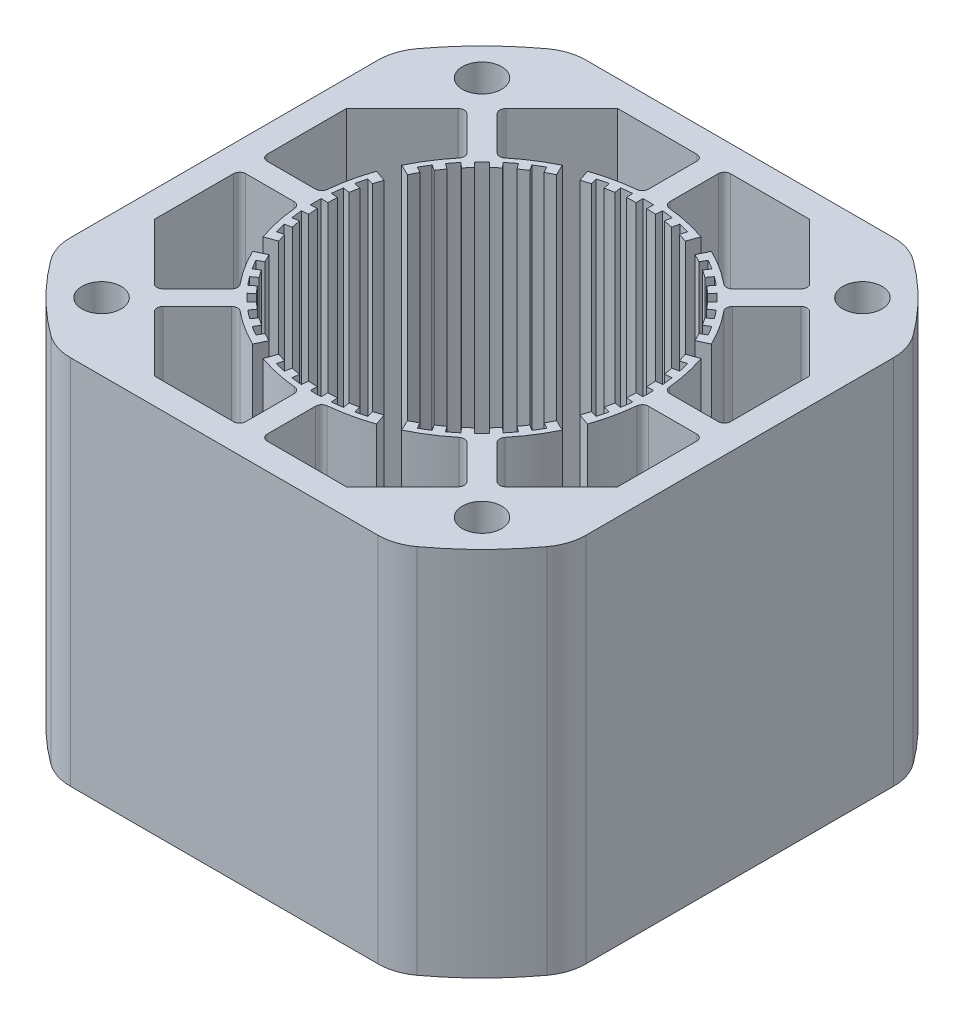
SolidWorks part; units mm, degrees
ref_plane "Front" through (0, 0, 0) normal (0, 0, 1) x (1, 0, 0)
ref_plane "Top" through (0, 0, 0) normal (0, 1, 0) x (1, 0, 0)
ref_plane "Right" through (0, 0, 0) normal (1, 0, 0) x (0, 0, -1)
ref_plane "Plane1" through (0, 10.95, 0) normal (0, 1, 0) x (1, 0, 0)
sketch "Sketch1" plane through (0, 10.95, 0) normal (0, 1, 0) x (1, 0, 0)
  line L0 (-0.875, -14.4347) -> (-0.875, -18.375)
  line L1 (-1.375, -18.875) -> (-7.8183, -18.875)
  line L2 (-7.8183, -18.875) -> (-12.3744, -14.3189)
  line L3 (-12.3744, -13.6118) -> (-9.5881, -10.8256)
  line L4 (-6.0745, -12.6135) -> (-5.6406, -11.7126)
  line L5 (-6.3066, -11.3678) -> (-6.5735, -11.8487)
  line L6 (-7.3337, -11.3938) -> (-7.036, -10.9313)
  line L7 (-7.6547, -10.5074) -> (-7.9786, -10.9519)
  line L8 (-8.6772, -10.4071) -> (-8.325, -9.9847)
  line L9 (-8.887, -9.488) -> (-9.2629, -9.8894)
  line L10 (-9.8894, -9.2629) -> (-9.488, -8.887)
  line L11 (-9.9847, -8.325) -> (-10.4071, -8.6772)
  line L12 (-10.9519, -7.9786) -> (-10.5074, -7.6547)
  line L13 (-10.9313, -7.036) -> (-11.3938, -7.3337)
  line L14 (-11.8487, -6.5735) -> (-11.3678, -6.3066)
  line L15 (-11.7126, -5.6406) -> (-12.6135, -6.0745)
  line L16 (-10.8256, -9.5881) -> (-13.6118, -12.3744)
  line L17 (-14.3189, -12.3744) -> (-18.875, -7.8183)
  line L18 (-18.875, -7.8183) -> (-18.875, -1.375)
  line L19 (-18.375, -0.875) -> (-14.4347, -0.875)
  line L20 (-13.2144, -4.6238) -> (-12.2705, -4.2935)
  line L21 (-12.4977, -3.5788) -> (-13.0264, -3.7302)
  line L22 (-13.2424, -2.8709) -> (-12.7049, -2.7544)
  line L23 (-12.8426, -2.0171) -> (-13.3859, -2.1025)
  line L24 (-13.4947, -1.2232) -> (-12.9469, -1.1736)
  line L25 (-12.9931, -0.425) -> (-13.5428, -0.443)
  line L26 (-13.5428, 0.443) -> (-12.9931, 0.425)
  line L27 (-12.9469, 1.1736) -> (-13.4947, 1.2232)
  line L28 (-13.3859, 2.1025) -> (-12.8426, 2.0171)
  line L29 (-12.7049, 2.7544) -> (-13.2424, 2.8709)
  line L30 (-13.0264, 3.7302) -> (-12.4977, 3.5788)
  line L31 (-12.2705, 4.2935) -> (-13.2144, 4.6238)
  line L32 (-14.4347, 0.875) -> (-18.375, 0.875)
  line L33 (-18.875, 1.375) -> (-18.875, 7.8183)
  line L34 (-18.875, 7.8183) -> (-14.3189, 12.3744)
  line L35 (-13.6118, 12.3744) -> (-10.8256, 9.5881)
  line L36 (-12.6135, 6.0745) -> (-11.7126, 5.6406)
  line L37 (-11.3678, 6.3066) -> (-11.8487, 6.5735)
  line L38 (-11.3938, 7.3337) -> (-10.9313, 7.036)
  line L39 (-10.5074, 7.6547) -> (-10.9519, 7.9786)
  line L40 (-10.4071, 8.6772) -> (-9.9847, 8.325)
  line L41 (-9.488, 8.887) -> (-9.8894, 9.2629)
  line L42 (-9.2629, 9.8894) -> (-8.887, 9.488)
  line L43 (-8.325, 9.9847) -> (-8.6772, 10.4071)
  line L44 (-7.9786, 10.9519) -> (-7.6547, 10.5074)
  line L45 (-7.036, 10.9313) -> (-7.3337, 11.3938)
  line L46 (-6.5735, 11.8487) -> (-6.3066, 11.3678)
  line L47 (-5.6406, 11.7126) -> (-6.0745, 12.6135)
  line L48 (-9.5881, 10.8256) -> (-12.3744, 13.6118)
  line L49 (-12.3744, 14.3189) -> (-7.8183, 18.875)
  line L50 (-7.8183, 18.875) -> (-1.375, 18.875)
  line L51 (-0.875, 18.375) -> (-0.875, 14.4347)
  line L52 (-4.6238, 13.2144) -> (-4.2935, 12.2705)
  line L53 (-3.5788, 12.4977) -> (-3.7302, 13.0264)
  line L54 (-2.8709, 13.2424) -> (-2.7544, 12.7049)
  line L55 (-2.0171, 12.8426) -> (-2.1025, 13.3859)
  line L56 (-1.2232, 13.4947) -> (-1.1736, 12.9469)
  line L57 (-0.425, 12.9931) -> (-0.443, 13.5428)
  line L58 (0.443, 13.5428) -> (0.425, 12.9931)
  line L59 (1.1736, 12.9469) -> (1.2232, 13.4947)
  line L60 (2.1025, 13.3859) -> (2.0171, 12.8426)
  line L61 (2.7544, 12.7049) -> (2.8709, 13.2424)
  line L62 (3.7302, 13.0264) -> (3.5788, 12.4977)
  line L63 (4.2935, 12.2705) -> (4.6238, 13.2144)
  line L64 (0.875, 14.4347) -> (0.875, 18.375)
  line L65 (1.375, 18.875) -> (7.8183, 18.875)
  line L66 (7.8183, 18.875) -> (12.3744, 14.3189)
  line L67 (12.3744, 13.6118) -> (9.5881, 10.8256)
  line L68 (6.0745, 12.6135) -> (5.6406, 11.7126)
  line L69 (6.3066, 11.3678) -> (6.5735, 11.8487)
  line L70 (7.3337, 11.3938) -> (7.036, 10.9313)
  line L71 (7.6547, 10.5074) -> (7.9786, 10.9519)
  line L72 (8.6772, 10.4071) -> (8.325, 9.9847)
  line L73 (8.887, 9.488) -> (9.2629, 9.8894)
  line L74 (9.8894, 9.2629) -> (9.488, 8.887)
  line L75 (9.9847, 8.325) -> (10.4071, 8.6772)
  line L76 (10.9519, 7.9786) -> (10.5074, 7.6547)
  line L77 (10.9313, 7.036) -> (11.3938, 7.3337)
  line L78 (11.8487, 6.5735) -> (11.3678, 6.3066)
  line L79 (11.7126, 5.6406) -> (12.6135, 6.0745)
  line L80 (10.8256, 9.5881) -> (13.6118, 12.3744)
  line L81 (14.3189, 12.3744) -> (18.875, 7.8183)
  line L82 (18.875, 7.8183) -> (18.875, 1.375)
  line L83 (18.375, 0.875) -> (14.4347, 0.875)
  line L84 (13.2144, 4.6238) -> (12.2705, 4.2935)
  line L85 (12.4977, 3.5788) -> (13.0264, 3.7302)
  line L86 (13.2424, 2.8709) -> (12.7049, 2.7544)
  line L87 (12.8426, 2.0171) -> (13.3859, 2.1025)
  line L88 (13.4947, 1.2232) -> (12.9469, 1.1736)
  line L89 (12.9931, 0.425) -> (13.5428, 0.443)
  line L90 (13.5428, -0.443) -> (12.9931, -0.425)
  line L91 (12.9469, -1.1736) -> (13.4947, -1.2232)
  line L92 (13.3859, -2.1025) -> (12.8426, -2.0171)
  line L93 (12.7049, -2.7544) -> (13.2424, -2.8709)
  line L94 (13.0264, -3.7302) -> (12.4977, -3.5788)
  line L95 (12.2705, -4.2935) -> (13.2144, -4.6238)
  line L96 (14.4347, -0.875) -> (18.375, -0.875)
  line L97 (18.875, -1.375) -> (18.875, -7.8183)
  line L98 (18.875, -7.8183) -> (14.3189, -12.3744)
  line L99 (13.6118, -12.3744) -> (10.8256, -9.5881)
  line L100 (12.6135, -6.0745) -> (11.7126, -5.6406)
  line L101 (11.3678, -6.3066) -> (11.8487, -6.5735)
  line L102 (11.3938, -7.3337) -> (10.9313, -7.036)
  line L103 (10.5074, -7.6547) -> (10.9519, -7.9786)
  line L104 (10.4071, -8.6772) -> (9.9847, -8.325)
  line L105 (9.488, -8.887) -> (9.8894, -9.2629)
  line L106 (9.2629, -9.8894) -> (8.887, -9.488)
  line L107 (8.325, -9.9847) -> (8.6772, -10.4071)
  line L108 (7.9786, -10.9519) -> (7.6547, -10.5074)
  line L109 (7.036, -10.9313) -> (7.3337, -11.3938)
  line L110 (6.5735, -11.8487) -> (6.3066, -11.3678)
  line L111 (5.6406, -11.7126) -> (6.0745, -12.6135)
  line L112 (9.5881, -10.8256) -> (12.3744, -13.6118)
  line L113 (12.3744, -14.3189) -> (7.8183, -18.875)
  line L114 (7.8183, -18.875) -> (1.375, -18.875)
  line L115 (0.875, -18.375) -> (0.875, -14.4347)
  line L116 (4.6238, -13.2144) -> (4.2935, -12.2705)
  line L117 (3.5788, -12.4977) -> (3.7302, -13.0264)
  line L118 (2.8709, -13.2424) -> (2.7544, -12.7049)
  line L119 (2.0171, -12.8426) -> (2.1025, -13.3859)
  line L120 (1.2232, -13.4947) -> (1.1736, -12.9469)
  line L121 (0.425, -12.9931) -> (0.443, -13.5428)
  line L122 (-0.443, -13.5428) -> (-0.425, -12.9931)
  line L123 (-1.1736, -12.9469) -> (-1.2232, -13.4947)
  line L124 (-2.1025, -13.3859) -> (-2.0171, -12.8426)
  line L125 (-2.7544, -12.7049) -> (-2.8709, -13.2424)
  line L126 (-3.7302, -13.0264) -> (-3.5788, -12.4977)
  line L127 (-4.2935, -12.2705) -> (-4.6238, -13.2144)
  line L128 (21, -12.5406) -> (21, 12.5406)
  line L129 (12.5406, 21) -> (-12.5406, 21)
  line L130 (-21, 12.5406) -> (-21, -12.5406)
  line L131 (-12.5406, -21) -> (12.5406, -21)
  arc A0 (-0.875, -18.375) -> (-1.375, -18.875) centre (-1.375, -18.375) cw
  arc A1 (-12.3744, -14.3189) -> (-12.3744, -13.6118) centre (-12.0208, -13.9654) cw
  arc A2 (-9.5881, -10.8256) -> (-8.9161, -10.7936) centre (-9.2346, -11.1791) cw
  arc A3 (-8.9161, -10.7936) -> (-6.0745, -12.6135) centre (0, 0) ccw
  arc A4 (-5.6406, -11.7126) -> (-6.3066, -11.3678) centre (0, 0) cw
  arc A5 (-6.5735, -11.8487) -> (-7.3337, -11.3938) centre (0, 0) cw
  arc A6 (-7.036, -10.9313) -> (-7.6547, -10.5074) centre (0, 0) cw
  arc A7 (-7.9786, -10.9519) -> (-8.6772, -10.4071) centre (0, 0) cw
  arc A8 (-8.325, -9.9847) -> (-8.887, -9.488) centre (0, 0) cw
  arc A9 (-9.2629, -9.8894) -> (-9.8894, -9.2629) centre (0, 0) cw
  arc A10 (-9.488, -8.887) -> (-9.9847, -8.325) centre (0, 0) cw
  arc A11 (-10.4071, -8.6772) -> (-10.9519, -7.9786) centre (0, 0) cw
  arc A12 (-10.5074, -7.6547) -> (-10.9313, -7.036) centre (0, 0) cw
  arc A13 (-11.3938, -7.3337) -> (-11.8487, -6.5735) centre (0, 0) cw
  arc A14 (-11.3678, -6.3066) -> (-11.7126, -5.6406) centre (0, 0) cw
  arc A15 (-12.6135, -6.0745) -> (-10.7936, -8.9161) centre (0, 0) ccw
  arc A16 (-10.7936, -8.9161) -> (-10.8256, -9.5881) centre (-11.1791, -9.2346) cw
  arc A17 (-13.6118, -12.3744) -> (-14.3189, -12.3744) centre (-13.9654, -12.0208) cw
  arc A18 (-18.875, -1.375) -> (-18.375, -0.875) centre (-18.375, -1.375) cw
  arc A19 (-14.4347, -0.875) -> (-13.9369, -1.3276) centre (-14.4347, -1.375) cw
  arc A20 (-13.9369, -1.3276) -> (-13.2144, -4.6238) centre (0, 0) ccw
  arc A21 (-12.2705, -4.2935) -> (-12.4977, -3.5788) centre (0, 0) cw
  arc A22 (-13.0264, -3.7302) -> (-13.2424, -2.8709) centre (0, 0) cw
  arc A23 (-12.7049, -2.7544) -> (-12.8426, -2.0171) centre (0, 0) cw
  arc A24 (-13.3859, -2.1025) -> (-13.4947, -1.2232) centre (0, 0) cw
  arc A25 (-12.9469, -1.1736) -> (-12.9931, -0.425) centre (0, 0) cw
  arc A26 (-13.5428, -0.443) -> (-13.5428, 0.443) centre (0, 0) cw
  arc A27 (-12.9931, 0.425) -> (-12.9469, 1.1736) centre (0, 0) cw
  arc A28 (-13.4947, 1.2232) -> (-13.3859, 2.1025) centre (0, 0) cw
  arc A29 (-12.8426, 2.0171) -> (-12.7049, 2.7544) centre (0, 0) cw
  arc A30 (-13.2424, 2.8709) -> (-13.0264, 3.7302) centre (0, 0) cw
  arc A31 (-12.4977, 3.5788) -> (-12.2705, 4.2935) centre (0, 0) cw
  arc A32 (-13.2144, 4.6238) -> (-13.9369, 1.3276) centre (0, 0) ccw
  arc A33 (-13.9369, 1.3276) -> (-14.4347, 0.875) centre (-14.4347, 1.375) cw
  arc A34 (-18.375, 0.875) -> (-18.875, 1.375) centre (-18.375, 1.375) cw
  arc A35 (-14.3189, 12.3744) -> (-13.6118, 12.3744) centre (-13.9654, 12.0208) cw
  arc A36 (-10.8256, 9.5881) -> (-10.7936, 8.9161) centre (-11.1791, 9.2346) cw
  arc A37 (-10.7936, 8.9161) -> (-12.6135, 6.0745) centre (0, 0) ccw
  arc A38 (-11.7126, 5.6406) -> (-11.3678, 6.3066) centre (0, 0) cw
  arc A39 (-11.8487, 6.5735) -> (-11.3938, 7.3337) centre (0, 0) cw
  arc A40 (-10.9313, 7.036) -> (-10.5074, 7.6547) centre (0, 0) cw
  arc A41 (-10.9519, 7.9786) -> (-10.4071, 8.6772) centre (0, 0) cw
  arc A42 (-9.9847, 8.325) -> (-9.488, 8.887) centre (0, 0) cw
  arc A43 (-9.8894, 9.2629) -> (-9.2629, 9.8894) centre (0, 0) cw
  arc A44 (-8.887, 9.488) -> (-8.325, 9.9847) centre (0, 0) cw
  arc A45 (-8.6772, 10.4071) -> (-7.9786, 10.9519) centre (0, 0) cw
  arc A46 (-7.6547, 10.5074) -> (-7.036, 10.9313) centre (0, 0) cw
  arc A47 (-7.3337, 11.3938) -> (-6.5735, 11.8487) centre (0, 0) cw
  arc A48 (-6.3066, 11.3678) -> (-5.6406, 11.7126) centre (0, 0) cw
  arc A49 (-6.0745, 12.6135) -> (-8.9161, 10.7936) centre (0, 0) ccw
  arc A50 (-8.9161, 10.7936) -> (-9.5881, 10.8256) centre (-9.2346, 11.1791) cw
  arc A51 (-12.3744, 13.6118) -> (-12.3744, 14.3189) centre (-12.0208, 13.9654) cw
  arc A52 (-1.375, 18.875) -> (-0.875, 18.375) centre (-1.375, 18.375) cw
  arc A53 (-0.875, 14.4347) -> (-1.3276, 13.9369) centre (-1.375, 14.4347) cw
  arc A54 (-1.3276, 13.9369) -> (-4.6238, 13.2144) centre (0, 0) ccw
  arc A55 (-4.2935, 12.2705) -> (-3.5788, 12.4977) centre (0, 0) cw
  arc A56 (-3.7302, 13.0264) -> (-2.8709, 13.2424) centre (0, 0) cw
  arc A57 (-2.7544, 12.7049) -> (-2.0171, 12.8426) centre (0, 0) cw
  arc A58 (-2.1025, 13.3859) -> (-1.2232, 13.4947) centre (0, 0) cw
  arc A59 (-1.1736, 12.9469) -> (-0.425, 12.9931) centre (0, 0) cw
  arc A60 (-0.443, 13.5428) -> (0.443, 13.5428) centre (0, 0) cw
  arc A61 (0.425, 12.9931) -> (1.1736, 12.9469) centre (0, 0) cw
  arc A62 (1.2232, 13.4947) -> (2.1025, 13.3859) centre (0, 0) cw
  arc A63 (2.0171, 12.8426) -> (2.7544, 12.7049) centre (0, 0) cw
  arc A64 (2.8709, 13.2424) -> (3.7302, 13.0264) centre (0, 0) cw
  arc A65 (3.5788, 12.4977) -> (4.2935, 12.2705) centre (0, 0) cw
  arc A66 (4.6238, 13.2144) -> (1.3276, 13.9369) centre (0, 0) ccw
  arc A67 (1.3276, 13.9369) -> (0.875, 14.4347) centre (1.375, 14.4347) cw
  arc A68 (0.875, 18.375) -> (1.375, 18.875) centre (1.375, 18.375) cw
  arc A69 (12.3744, 14.3189) -> (12.3744, 13.6118) centre (12.0208, 13.9654) cw
  arc A70 (9.5881, 10.8256) -> (8.9161, 10.7936) centre (9.2346, 11.1791) cw
  arc A71 (8.9161, 10.7936) -> (6.0745, 12.6135) centre (0, 0) ccw
  arc A72 (5.6406, 11.7126) -> (6.3066, 11.3678) centre (0, 0) cw
  arc A73 (6.5735, 11.8487) -> (7.3337, 11.3938) centre (0, 0) cw
  arc A74 (7.036, 10.9313) -> (7.6547, 10.5074) centre (0, 0) cw
  arc A75 (7.9786, 10.9519) -> (8.6772, 10.4071) centre (0, 0) cw
  arc A76 (8.325, 9.9847) -> (8.887, 9.488) centre (0, 0) cw
  arc A77 (9.2629, 9.8894) -> (9.8894, 9.2629) centre (0, 0) cw
  arc A78 (9.488, 8.887) -> (9.9847, 8.325) centre (0, 0) cw
  arc A79 (10.4071, 8.6772) -> (10.9519, 7.9786) centre (0, 0) cw
  arc A80 (10.5074, 7.6547) -> (10.9313, 7.036) centre (0, 0) cw
  arc A81 (11.3938, 7.3337) -> (11.8487, 6.5735) centre (0, 0) cw
  arc A82 (11.3678, 6.3066) -> (11.7126, 5.6406) centre (0, 0) cw
  arc A83 (12.6135, 6.0745) -> (10.7936, 8.9161) centre (0, 0) ccw
  arc A84 (10.7936, 8.9161) -> (10.8256, 9.5881) centre (11.1791, 9.2346) cw
  arc A85 (13.6118, 12.3744) -> (14.3189, 12.3744) centre (13.9654, 12.0208) cw
  arc A86 (18.875, 1.375) -> (18.375, 0.875) centre (18.375, 1.375) cw
  arc A87 (14.4347, 0.875) -> (13.9369, 1.3276) centre (14.4347, 1.375) cw
  arc A88 (13.9369, 1.3276) -> (13.2144, 4.6238) centre (0, 0) ccw
  arc A89 (12.2705, 4.2935) -> (12.4977, 3.5788) centre (0, 0) cw
  arc A90 (13.0264, 3.7302) -> (13.2424, 2.8709) centre (0, 0) cw
  arc A91 (12.7049, 2.7544) -> (12.8426, 2.0171) centre (0, 0) cw
  arc A92 (13.3859, 2.1025) -> (13.4947, 1.2232) centre (0, 0) cw
  arc A93 (12.9469, 1.1736) -> (12.9931, 0.425) centre (0, 0) cw
  arc A94 (13.5428, 0.443) -> (13.5428, -0.443) centre (0, 0) cw
  arc A95 (12.9931, -0.425) -> (12.9469, -1.1736) centre (0, 0) cw
  arc A96 (13.4947, -1.2232) -> (13.3859, -2.1025) centre (0, 0) cw
  arc A97 (12.8426, -2.0171) -> (12.7049, -2.7544) centre (0, 0) cw
  arc A98 (13.2424, -2.8709) -> (13.0264, -3.7302) centre (0, 0) cw
  arc A99 (12.4977, -3.5788) -> (12.2705, -4.2935) centre (0, 0) cw
  arc A100 (13.2144, -4.6238) -> (13.9369, -1.3276) centre (0, 0) ccw
  arc A101 (13.9369, -1.3276) -> (14.4347, -0.875) centre (14.4347, -1.375) cw
  arc A102 (18.375, -0.875) -> (18.875, -1.375) centre (18.375, -1.375) cw
  arc A103 (14.3189, -12.3744) -> (13.6118, -12.3744) centre (13.9654, -12.0208) cw
  arc A104 (10.8256, -9.5881) -> (10.7936, -8.9161) centre (11.1791, -9.2346) cw
  arc A105 (10.7936, -8.9161) -> (12.6135, -6.0745) centre (0, 0) ccw
  arc A106 (11.7126, -5.6406) -> (11.3678, -6.3066) centre (0, 0) cw
  arc A107 (11.8487, -6.5735) -> (11.3938, -7.3337) centre (0, 0) cw
  arc A108 (10.9313, -7.036) -> (10.5074, -7.6547) centre (0, 0) cw
  arc A109 (10.9519, -7.9786) -> (10.4071, -8.6772) centre (0, 0) cw
  arc A110 (9.9847, -8.325) -> (9.488, -8.887) centre (0, 0) cw
  arc A111 (9.8894, -9.2629) -> (9.2629, -9.8894) centre (0, 0) cw
  arc A112 (8.887, -9.488) -> (8.325, -9.9847) centre (0, 0) cw
  arc A113 (8.6772, -10.4071) -> (7.9786, -10.9519) centre (0, 0) cw
  arc A114 (7.6547, -10.5074) -> (7.036, -10.9313) centre (0, 0) cw
  arc A115 (7.3337, -11.3938) -> (6.5735, -11.8487) centre (0, 0) cw
  arc A116 (6.3066, -11.3678) -> (5.6406, -11.7126) centre (0, 0) cw
  arc A117 (6.0745, -12.6135) -> (8.9161, -10.7936) centre (0, 0) ccw
  arc A118 (8.9161, -10.7936) -> (9.5881, -10.8256) centre (9.2346, -11.1791) cw
  arc A119 (12.3744, -13.6118) -> (12.3744, -14.3189) centre (12.0208, -13.9654) cw
  arc A120 (1.375, -18.875) -> (0.875, -18.375) centre (1.375, -18.375) cw
  arc A121 (0.875, -14.4347) -> (1.3276, -13.9369) centre (1.375, -14.4347) cw
  arc A122 (1.3276, -13.9369) -> (4.6238, -13.2144) centre (0, 0) ccw
  arc A123 (4.2935, -12.2705) -> (3.5788, -12.4977) centre (0, 0) cw
  arc A124 (3.7302, -13.0264) -> (2.8709, -13.2424) centre (0, 0) cw
  arc A125 (2.7544, -12.7049) -> (2.0171, -12.8426) centre (0, 0) cw
  arc A126 (2.1025, -13.3859) -> (1.2232, -13.4947) centre (0, 0) cw
  arc A127 (1.1736, -12.9469) -> (0.425, -12.9931) centre (0, 0) cw
  arc A128 (0.443, -13.5428) -> (-0.443, -13.5428) centre (0, 0) cw
  arc A129 (-0.425, -12.9931) -> (-1.1736, -12.9469) centre (0, 0) cw
  arc A130 (-1.2232, -13.4947) -> (-2.1025, -13.3859) centre (0, 0) cw
  arc A131 (-2.0171, -12.8426) -> (-2.7544, -12.7049) centre (0, 0) cw
  arc A132 (-2.8709, -13.2424) -> (-3.7302, -13.0264) centre (0, 0) cw
  arc A133 (-3.5788, -12.4977) -> (-4.2935, -12.2705) centre (0, 0) cw
  arc A134 (-4.6238, -13.2144) -> (-1.3276, -13.9369) centre (0, 0) ccw
  arc A135 (-1.3276, -13.9369) -> (-0.875, -14.4347) centre (-1.375, -14.4347) cw
  arc A136 (14.9151, -20.2189) -> (20.2189, -14.9151) centre (0, 0) ccw
  arc A137 (20.2189, -14.9151) -> (21, -12.5406) centre (17, -12.5406) ccw
  arc A138 (21, 12.5406) -> (20.2189, 14.9151) centre (17, 12.5406) ccw
  arc A139 (20.2189, 14.9151) -> (14.9151, 20.2189) centre (0, 0) ccw
  arc A140 (14.9151, 20.2189) -> (12.5406, 21) centre (12.5406, 17) ccw
  arc A141 (-12.5406, 21) -> (-14.9151, 20.2189) centre (-12.5406, 17) ccw
  arc A142 (-14.9151, 20.2189) -> (-20.2189, 14.9151) centre (0, 0) ccw
  arc A143 (-20.2189, 14.9151) -> (-21, 12.5406) centre (-17, 12.5406) ccw
  arc A144 (-21, -12.5406) -> (-20.2189, -14.9151) centre (-17, -12.5406) ccw
  arc A145 (-20.2189, -14.9151) -> (-14.9151, -20.2189) centre (0, 0) ccw
  arc A146 (-14.9151, -20.2189) -> (-12.5406, -21) centre (-12.5406, -17) ccw
  arc A147 (12.5406, -21) -> (14.9151, -20.2189) centre (12.5406, -17) ccw
sketch "Sketch10" plane through (0, 0, 0) normal (0, 1, 0) x (1, 0, 0)
  line L4 (12.5406, 21) -> (-12.5406, 21)
  line L5 (-21, 12.5406) -> (-21, -12.5406)
  line L6 (-12.5406, -21) -> (12.5406, -21)
  line L7 (21, -12.5406) -> (21, 12.5406)
  line L10 (7.8183, -18.875) -> (18.875, -7.8183)
  line L11 (18.875, -7.8183) -> (18.875, 7.8183)
  line L12 (18.875, 7.8183) -> (7.8183, 18.875)
  line L13 (7.8183, 18.875) -> (-7.8183, 18.875)
  line L14 (-7.8183, 18.875) -> (-18.875, 7.8183)
  line L15 (-18.875, 7.8183) -> (-18.875, -7.8183)
  line L16 (-18.875, -7.8183) -> (-7.8183, -18.875)
  line L17 (0, 21) -> (0, 0) construction
  line L18 (0, 0) -> (21, 0) construction
  line L19 (-7.8183, -18.875) -> (7.8183, -18.875)
  arc A12 (-12.5406, 21) -> (-14.9151, 20.2189) centre (-12.5406, 17) ccw
  arc A13 (-14.9151, 20.2189) -> (-20.2189, 14.9151) centre (0, 0) ccw
  arc A14 (-20.2189, 14.9151) -> (-21, 12.5406) centre (-17, 12.5406) ccw
  arc A15 (-21, -12.5406) -> (-20.2189, -14.9151) centre (-17, -12.5406) ccw
  arc A16 (-20.2189, -14.9151) -> (-14.9151, -20.2189) centre (0, 0) ccw
  arc A17 (-14.9151, -20.2189) -> (-12.5406, -21) centre (-12.5406, -17) ccw
  arc A18 (12.5406, -21) -> (14.9151, -20.2189) centre (12.5406, -17) ccw
  arc A19 (14.9151, -20.2189) -> (20.2189, -14.9151) centre (0, 0) ccw
  arc A20 (20.2189, -14.9151) -> (21, -12.5406) centre (17, -12.5406) ccw
  arc A21 (21, 12.5406) -> (20.2189, 14.9151) centre (17, 12.5406) ccw
  arc A22 (20.2189, 14.9151) -> (14.9151, 20.2189) centre (0, 0) ccw
  arc A23 (14.9151, 20.2189) -> (12.5406, 21) centre (12.5406, 17) ccw
  circle A24 centre (0, 0) radius 18.875 construction
  point P26 (-15.5, 15.5)
  point P39 (15.5, 15.5)
  point P40 (15.5, -15.5)
  point P41 (-15.5, -15.5)
  dimension "D3" = 25.125
  dimension "D4" = 4
  dimension "D1" = 42
  dimension "D2" = 42
  dimension "D5" = 37.75
  dimension "D6" = 31
  dimension "D7" = 31
extrude "Boss-Extrude2" add sketch "Sketch10" along normal mid plane 30.25
sketch "Sketch11" plane through (0, 0, 0) normal (0, 1, 0) x (1, 0, 0)
  line L1 (0, 0) -> (0, 24.4906) construction
  line L3 (-0.875, 18.375) -> (-0.875, 14.4347)
  line L5 (0.875, 14.4347) -> (0.875, 18.375)
  line L17 (4.2935, 12.2705) -> (4.6238, 13.2144)
  line L18 (3.7302, 13.0264) -> (3.5788, 12.4977)
  line L19 (2.7544, 12.7049) -> (2.8709, 13.2424)
  line L20 (2.1025, 13.3859) -> (2.0171, 12.8426)
  line L21 (1.1736, 12.9469) -> (1.2232, 13.4947)
  line L22 (0.443, 13.5428) -> (0.425, 12.9931)
  line L23 (-0.425, 12.9931) -> (-0.443, 13.5428)
  line L24 (-1.1736, 12.9469) -> (-1.2232, 13.4947)
  line L25 (-2.1025, 13.3859) -> (-2.0171, 12.8426)
  line L26 (-2.7544, 12.7049) -> (-2.8709, 13.2424)
  line L27 (-3.7302, 13.0264) -> (-3.5788, 12.4977)
  line L28 (-4.6238, 13.2144) -> (-4.2935, 12.2705)
  line L29 (1.375, 18.875) -> (-1.375, 18.875)
  line L30 (7.8183, 18.875) -> (-7.8183, 18.875) construction
  arc A0 (4.6238, 13.2144) -> (1.3276, 13.9369) centre (0, 0) ccw
  arc A4 (-0.875, 18.375) -> (-1.375, 18.875) centre (-1.375, 18.375) ccw
  arc A5 (-1.3276, 13.9369) -> (-0.875, 14.4347) centre (-1.375, 14.4347) ccw
  arc A8 (1.375, 18.875) -> (0.875, 18.375) centre (1.375, 18.375) ccw
  arc A9 (0.875, 14.4347) -> (1.3276, 13.9369) centre (1.375, 14.4347) ccw
  arc A21 (4.2935, 12.2705) -> (3.5788, 12.4977) centre (0, 0) ccw
  arc A22 (3.7302, 13.0264) -> (2.8709, 13.2424) centre (0, 0) ccw
  arc A23 (2.7544, 12.7049) -> (2.0171, 12.8426) centre (0, 0) ccw
  arc A24 (2.1025, 13.3859) -> (1.2232, 13.4947) centre (0, 0) ccw
  arc A25 (1.1736, 12.9469) -> (0.425, 12.9931) centre (0, 0) ccw
  arc A26 (0.443, 13.5428) -> (-0.443, 13.5428) centre (0, 0) ccw
  arc A27 (-0.425, 12.9931) -> (-1.1736, 12.9469) centre (0, 0) ccw
  arc A28 (-1.2232, 13.4947) -> (-2.1025, 13.3859) centre (0, 0) ccw
  arc A29 (-2.0171, 12.8426) -> (-2.7544, 12.7049) centre (0, 0) ccw
  arc A30 (-2.8709, 13.2424) -> (-3.7302, 13.0264) centre (0, 0) ccw
  arc A31 (-3.5788, 12.4977) -> (-4.2935, 12.2705) centre (0, 0) ccw
  arc A32 (-1.3276, 13.9369) -> (-4.6238, 13.2144) centre (0, 0) ccw
  dimension "D2" = 0.5
  dimension "D3" = 14
  dimension "D4" = 1
  dimension "D5" = 0.45
  dimension "D1" = 1.75
  dimension "D6" = 0.85
  dimension "D7" = 0.85
  dimension "D8" = 0.75
  dimension "D9" = 0.75
  dimension "D10" = 0.85
  dimension "D11" = 0.75
extrude "Boss-Extrude3" add sketch "Sketch11" along normal up to vertex (15.125 mm away) from vertex at -15.125 starting at point (7.8183, -15.125, -18.875)
pattern_circular "CirPattern1" count 8 over 360 about axis through (0, 0, 0) along (0, 1, 0) of "Boss-Extrude3"
hole_wizard "Ø3.2 (3.2) Diameter Hole1" positions "Sketch3" profile "Sketch2" hole size "Ø3.2" standard "ANSI Metric" end condition through all
sketch "Sketch3" plane through (0, 15.125, 0) normal (0, -1, 0) x (-1, 0, 0)
  point P0 (-15.5, -15.5)
  point P1 (-15.5, 15.5)
  point P4 (15.5, 15.5)
  point P7 (15.5, -15.5)
sketch "Sketch2" plane through (15.5, 15.125, 15.5) normal (1, 0, 0) x (0, 0, 1)
  line L0 (0, 0) -> (0, 30.25)
  line L1 (0, 30.25) -> (1.6, 30.25)
  line L2 (1.6, 30.25) -> (1.6, 0)
  line L5 (1.6, 0) -> (0, 0)
  line L11 (0, -6.35) -> (0, 107.95) construction
  dimension "Thru Hole Dia." = 3.2
  dimension "Thru Hole Depth" = 30.25
